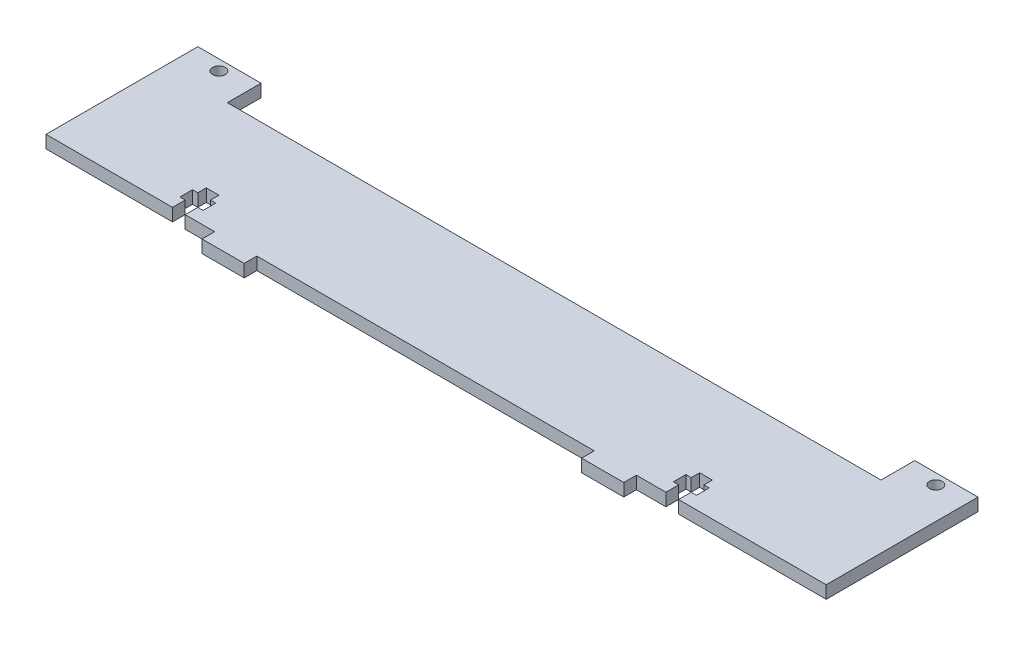
SolidWorks part; units mm, degrees
ref_plane "Front Plane" through (0, 0, 0) normal (0, 0, 1) x (1, 0, 0)
ref_plane "Top Plane" through (0, 0, 0) normal (0, 1, 0) x (1, 0, 0)
ref_plane "Right Plane" through (0, 0, 0) normal (1, 0, 0) x (0, 0, -1)
sketch "Sketch1" plane through (0, 0, 0) normal (0, 1, 0) x (1, 0, 0)
  line L1 (-110, -19.5) -> (110, -19.5)
  line L2 (-110, -19.5) -> (-110, 19.5)
  line L3 (-110, 19.5) -> (110, 19.5)
  line L4 (110, -19.5) -> (110, 19.5)
  line L5 (-110, -19.5) -> (110, 19.5) construction
  line L6 (-110, 19.5) -> (110, -19.5) construction
  point P0 (0, 0)
  dimension "D1" = 39
  dimension "D2" = 220
extrude "Boss-Extrude1" add sketch "Sketch1" along normal blind 3
sketch "Sketch2" plane through (0, 0, 0) normal (0, -1, 0) x (1, 0, 0)
  line L1 (-80, 16.5) -> (-80, 13.5)
  line L3 (110, -19.5) -> (-110, -19.5) construction
  line L6 (-95, -19.5) -> (-95, -11.5)
  line L10 (75, 19.5) -> (75, -19.5)
  line L11 (-110, -19.5) -> (-110, 19.5) construction
  line L19 (-110, 19.5) -> (110, 19.5) construction
  line L20 (75, -19.5) -> (110, -19.5)
  line L21 (110, -19.5) -> (110, 19.5)
  line L22 (110, 19.5) -> (110, -19.5) construction
  line L23 (110, 19.5) -> (75, 19.5)
  line L24 (-95, -11.5) -> (60, -11.5)
  line L25 (60, -11.5) -> (60, -19.5)
  line L26 (60, -19.5) -> (-95, -19.5)
  line L29 (75, -13) -> (75, -19.5)
  line L55 (-110, 19.5) -> (-70, 19.5)
  line L56 (-110, 19.5) -> (-110, 16.5)
  line L57 (-110, 16.5) -> (-70, 16.5)
  line L58 (-70, 19.5) -> (-70, 16.5)
  line L59 (-60, 19.5) -> (20, 19.5)
  line L60 (-60, 19.5) -> (-60, 16.5)
  line L61 (-60, 16.5) -> (20, 16.5)
  line L62 (20, 19.5) -> (20, 16.5)
  line L63 (75, 19.5) -> (30, 19.5)
  line L64 (75, 19.5) -> (75, 16.5)
  line L65 (75, 16.5) -> (30, 16.5)
  line L66 (30, 19.5) -> (30, 16.5)
  line L67 (-80, 13.5) -> (-81.25, 13.5)
  line L68 (-81.25, 13.5) -> (-81.25, 10.5)
  line L69 (-81.25, 10.5) -> (-80, 10.5)
  line L70 (-80, 10.5) -> (-80, 8.5)
  line L71 (-80, 8.5) -> (-77, 8.5)
  line L72 (-77, 8.5) -> (-77, 10.5)
  line L73 (-77, 10.5) -> (-75.75, 10.5)
  line L74 (-75.75, 10.5) -> (-75.75, 13.5)
  line L75 (-75.75, 13.5) -> (-77, 13.5)
  line L76 (-77, 13.5) -> (-77, 16.5)
  line L77 (-77, 16.5) -> (-80, 16.5)
  line L78 (37, 16.5) -> (37, 13.5)
  line L79 (37, 13.5) -> (35.75, 13.5)
  line L80 (35.75, 13.5) -> (35.75, 10.5)
  line L81 (35.75, 10.5) -> (37, 10.5)
  line L82 (37, 10.5) -> (37, 8.5)
  line L83 (37, 8.5) -> (40, 8.5)
  line L84 (40, 8.5) -> (40, 10.5)
  line L85 (40, 10.5) -> (41.25, 10.5)
  line L86 (41.25, 10.5) -> (41.25, 13.5)
  line L87 (41.25, 13.5) -> (40, 13.5)
  line L88 (40, 13.5) -> (40, 16.5)
  line L89 (40, 16.5) -> (37, 16.5)
  circle A0 centre (-102.5, -17) radius 1.5
  circle A1 centre (67.5, -17) radius 1.5
  line M12 (-110, -19.5) -> (110, -19.5)
  dimension "D6" = 3
  dimension "D13" = 3
  dimension "D15" = 2.5
  dimension "D2" = 35
  dimension "D3" = 15
  dimension "D4" = 15
  dimension "D5" = 8
  dimension "D7" = 7.5
  dimension "D8" = 3
  dimension "D9" = 40
  dimension "D10" = 10
  dimension "D11" = 10
  dimension "D12" = 80
  dimension "D14" = 7.5
  dimension "D16" = 2.5
  dimension "D17" = 3
  dimension "D18" = 3
  dimension "D19" = 2
  dimension "D20" = 3
  dimension "D21" = 1.25
  dimension "D22" = 3
  dimension "D23" = 3
  dimension "D24" = 5.5
  dimension "D25" = 3
  dimension "D26" = 30
  dimension "D27" = 3
  dimension "D28" = 2
  dimension "D29" = 1.25
  dimension "D30" = 3
  dimension "D31" = 35
extrude "Cut-Extrude2" cut sketch "Sketch2" against normal blind 3 contours L25 L24 L6 M12
